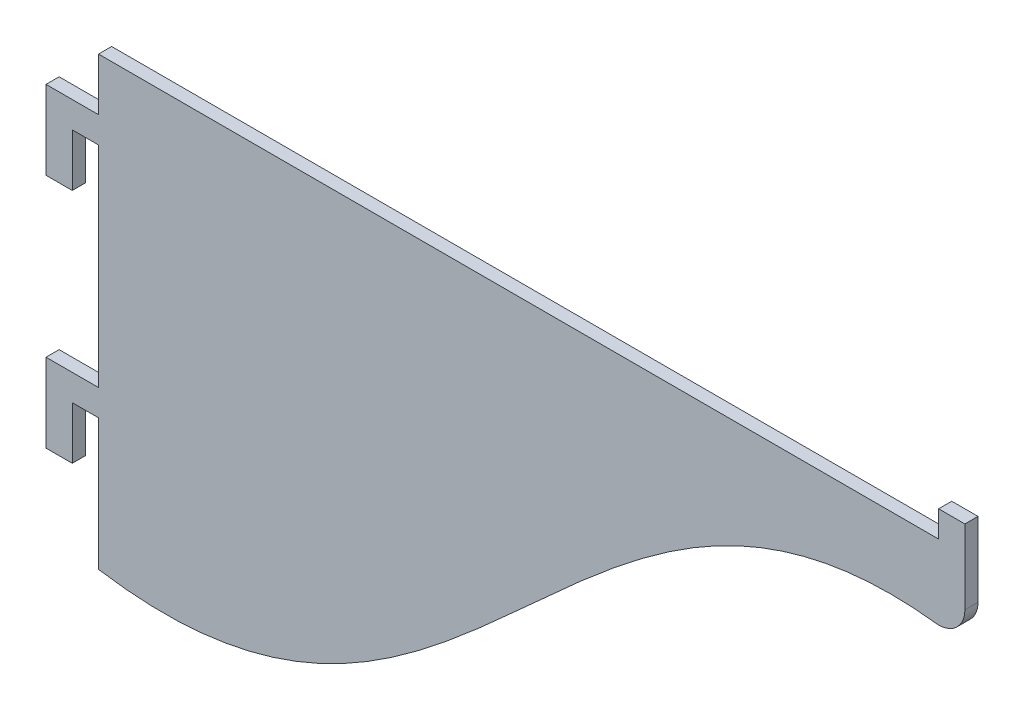
SolidWorks part; units mm, degrees
ref_plane "Front Plane" through (0, 0, 0) normal (0, 0, 1) x (1, 0, 0)
ref_plane "Top Plane" through (0, 0, 0) normal (0, 1, 0) x (1, 0, 0)
ref_plane "Right Plane" through (0, 0, 0) normal (1, 0, 0) x (0, 0, -1)
sketch "Sketch1" plane through (0, 0, 0) normal (0, 0, 1) x (1, 0, 0)
  line L0 (0, 0) -> (0, -12.7)
  line L1 (0, -55) -> (0, 55) construction
  line L2 (0, 0) -> (203.2, 0)
  line L3 (55, 0) -> (-55, 0) construction
  line L4 (203.2, 0) -> (203.2, 6.35)
  line L5 (203.2, 6.35) -> (209.55, 6.35)
  line L6 (209.55, 6.35) -> (209.55, -11.644)
  line L7 (0, -12.7) -> (-12.7, -12.7)
  line L8 (-12.7, -12.7) -> (-12.7, -31.75)
  line L9 (-12.7, -31.75) -> (-6.35, -31.75)
  line L10 (-6.35, -31.75) -> (-6.35, -19.05)
  line L11 (-6.35, -19.05) -> (0, -19.05)
  line L12 (0, -69.85) -> (-12.7, -69.85)
  line L13 (-12.7, -69.85) -> (-12.7, -88.9)
  line L14 (-12.7, -88.9) -> (-6.35, -88.9)
  line L15 (-6.35, -88.9) -> (-6.35, -76.2)
  line L16 (-6.35, -76.2) -> (0, -76.2)
  line L17 (0, -19.05) -> (0, -69.85)
  line L18 (0, -76.2) -> (0, -107.95)
  arc A0 (202.4484, -17.9494) -> (209.55, -11.644) centre (203.2, -11.644) ccw
  spline S0 degree 3 poles (0, -107.95) (64.9729, -118.2489) (107.2608, -42.0408) (176.7202, -14.8825) (202.4484, -17.9494) knots 0 0 0 0 0.687412 0.974132 0.974132 0.974132 0.974132
  dimension "D16" = 6.35
  dimension "D2" = 6.35
  dimension "D3" = 6.35
  dimension "D4" = 203.2
  dimension "D5" = 107.95
  dimension "D6" = 12.7
  dimension "D7" = 6.35
  dimension "D8" = 19.05
  dimension "D9" = 12.7
  dimension "D10" = 12.7
  dimension "D11" = 19.05
  dimension "D12" = 12.7
  dimension "D13" = 12.7
  dimension "D14" = 6.35
  dimension "D15" = 69.85
extrude "Boss-Extrude1" add sketch "Sketch1" along normal blind 3.175
